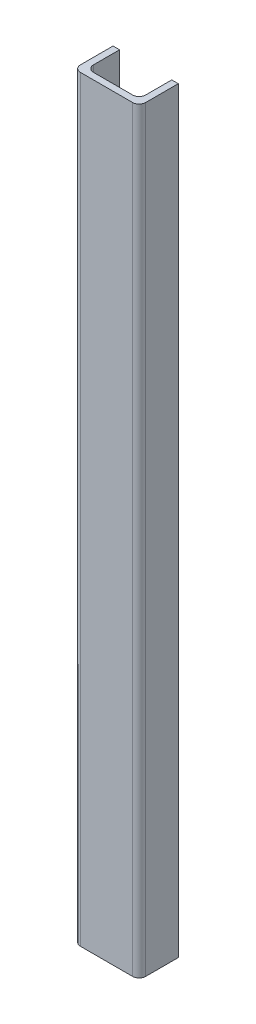
SolidWorks part; units mm, degrees
ref_plane "Front Plane" through (0, 0, 0) normal (0, 0, 1) x (1, 0, 0)
ref_plane "Top Plane" through (0, 0, 0) normal (0, 1, 0) x (1, 0, 0)
ref_plane "Right Plane" through (0, 0, 0) normal (1, 0, 0) x (0, 0, -1)
sketch "Sketch1" plane through (0, 0, 0) normal (0, 1, 0) x (1, 0, 0)
  line L5 (-15, 2.5) -> (15, 2.5)
  line L7 (-20, -2.5) -> (20, -2.5)
  line L9 (-25, 27.5) -> (-20, 27.5)
  line L10 (-25, 27.5) -> (-25, 2.5)
  line L12 (-20, 27.5) -> (-20, 7.5)
  line L14 (25, 2.5) -> (25, 27.5)
  line L15 (25, 27.5) -> (20, 27.5)
  line L16 (20, 7.5) -> (20, 27.5)
  arc A0 (15, 2.5) -> (20, 7.5) centre (15, 7.5) ccw
  arc A1 (-15, 2.5) -> (-20, 7.5) centre (-15, 7.5) cw
  arc A2 (20, -2.5) -> (25, 2.5) centre (20, 2.5) ccw
  arc A3 (-25, 2.5) -> (-20, -2.5) centre (-20, 2.5) ccw
  point P2 (0, 0)
  point P16 (0, 0)
  point P18 (25, -2.5)
  point P21 (-25, -2.5)
  dimension "D9" = 5
  dimension "D8" = 5
  dimension "D1" = 50
  dimension "D2" = 30
  dimension "D3" = 25
  dimension "D4" = 2.5
  dimension "D5" = 5
  dimension "D6" = 30
  dimension "D7" = 5
extrude "Boss-Extrude2" add sketch "Sketch1" along normal blind 580
